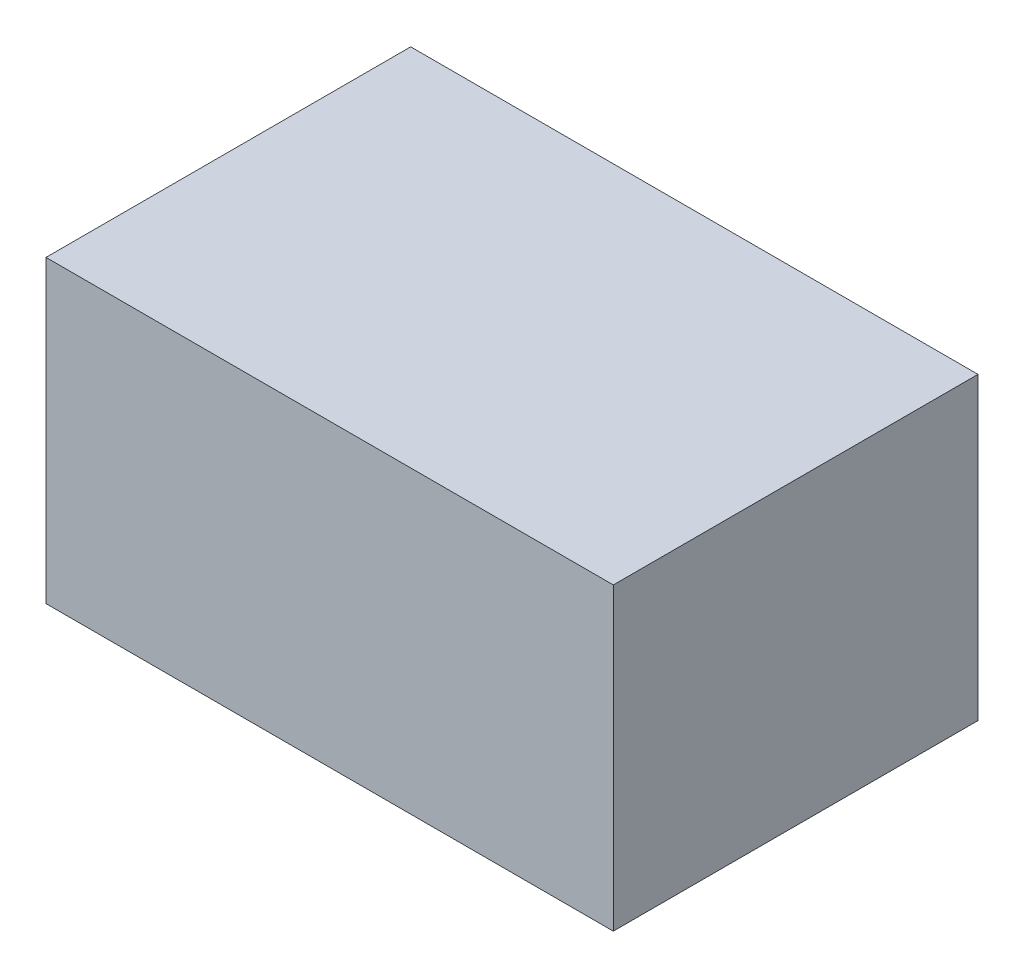
SolidWorks part; units mm, degrees
ref_plane "Front Plane" through (0, 0, 0) normal (0, 0, 1) x (1, 0, 0)
ref_plane "Top Plane" through (0, 0, 0) normal (0, 1, 0) x (1, 0, 0)
ref_plane "Right Plane" through (0, 0, 0) normal (1, 0, 0) x (0, 0, -1)
sketch "Sketch1" plane through (0, 0, 0) normal (0, 1, 0) x (1, 0, 0)
  line L1 (0, 0) -> (7, 0)
  line L2 (0, 0) -> (0, 4.5)
  line L3 (0, 4.5) -> (7, 4.5)
  line L4 (7, 0) -> (7, 4.5)
  dimension "D1" = 4.5
  dimension "D2" = 7
extrude "Boss-Extrude1" add sketch "Sketch1" along normal blind 3.7
